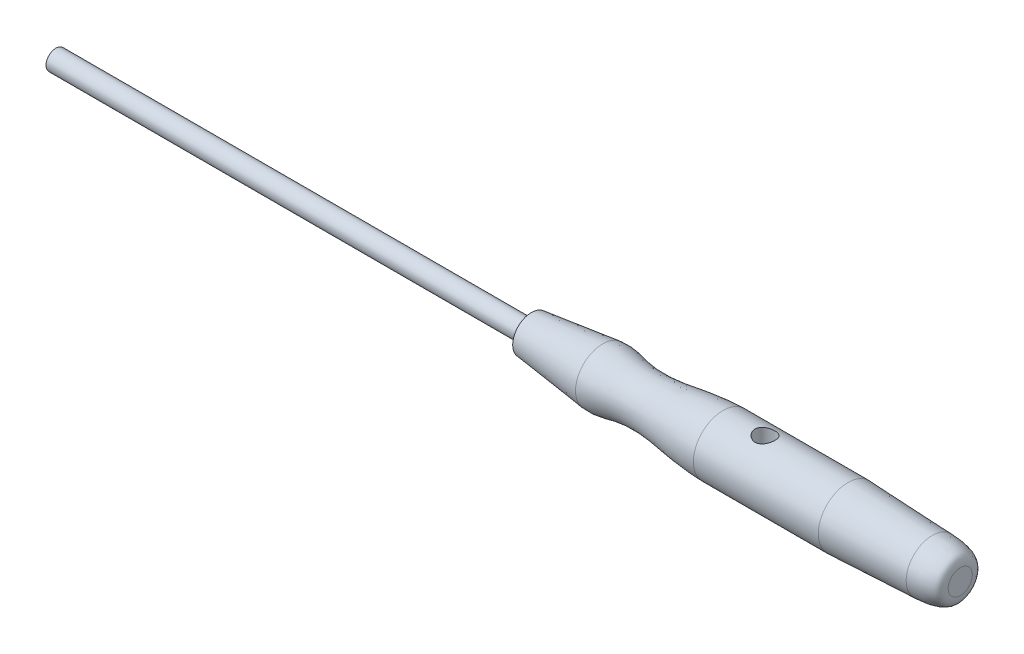
SolidWorks part; units mm, degrees
ref_plane "Front Plane" through (0, 0, 0) normal (0, 0, 1) x (1, 0, 0)
ref_plane "Top Plane" through (0, 0, 0) normal (0, 1, 0) x (1, 0, 0)
ref_plane "Right Plane" through (0, 0, 0) normal (1, 0, 0) x (0, 0, -1)
sketch "Sketch1" plane through (0, 0, 0) normal (0, 0, 1) x (1, 0, 0)
  line L0 (-137.5, 0) -> (137.5, 0)
  line L1 (-137.5, 11.938) -> (-137.5, 0)
  line L2 (-91.78, 17.399) -> (-91.78, 0) construction
  line L3 (-72.984, 15.24) -> (-72.984, 0) construction
  line L4 (-14.564, 19.05) -> (-14.564, 0) construction
  line L5 (-137.5, 11.938) -> (-91.78, 17.399)
  line L6 (119.602, 0) -> (119.602, 16.764) construction
  line L7 (65.5, 0) -> (65.5, 19.05) construction
  line L8 (65.5, 19.05) -> (119.602, 16.764)
  line L9 (-14.564, 19.05) -> (65.5, 19.05)
  line L10 (133.826, 14.351) -> (133.826, 0) construction
  line L11 (137.5, 0) -> (137.5, 7.747) construction
  line L12 (137.5, 7.747) -> (137.5, 0)
  spline S0 degree 3 poles (-91.78, 17.399) (-84.9013, 18.2206) (-60.5493, 10.0128) (-35.8294, 19.05) (-14.564, 19.05) knots 0 0 0 0 0.244238 1 1 1 1
  spline S1 degree 3 poles (119.602, 16.764) (126.4467, 16.4748) (132.2517, 15.7308) (137.5, 12.3228) (137.5, 7.747) knots 0 0 0 0 0.656248 1 1 1 1
  point P16 (0, 0)
  dimension "D2" = 45.72
  dimension "D3" = 11.938
  dimension "D1" = 16.764
  dimension "D4" = 64.516
  dimension "D5" = 15.24
  dimension "D6" = 19.05
  dimension "D7" = 122.936
  dimension "D8" = 203
  dimension "D9" = 19.05
  dimension "D10" = 54.102
  dimension "D11" = 275
  dimension "D12" = 14.351
  dimension "D13" = 7.747
  dimension "D14" = 14.224
  dimension "D15" = 17.399
revolve "Revolve1" add sketch "Sketch1" angle 360 about L0
sketch "Sketch3" plane through (0, 0, 0) normal (0, 1, 0) x (1, 0, 0)
  line L0 (-137.5, 11.938) -> (-137.5, -11.938) construction
  circle A0 centre (12.36, 0) radius 6.35
  dimension "D1" = 12.7
  dimension "D2" = 149.86
extrude "Cut-Extrude1" cut sketch "Sketch3" along normal up to next
sketch "Sketch6" plane through (-137.5, 0, 0) normal (-1, 0, 0) x (0, 0, 1)
  circle A0 centre (0, 0) radius 6.35
  dimension "D1" = 12.7
extrude "Boss-Extrude1" add sketch "Sketch6" along normal blind 304.8
